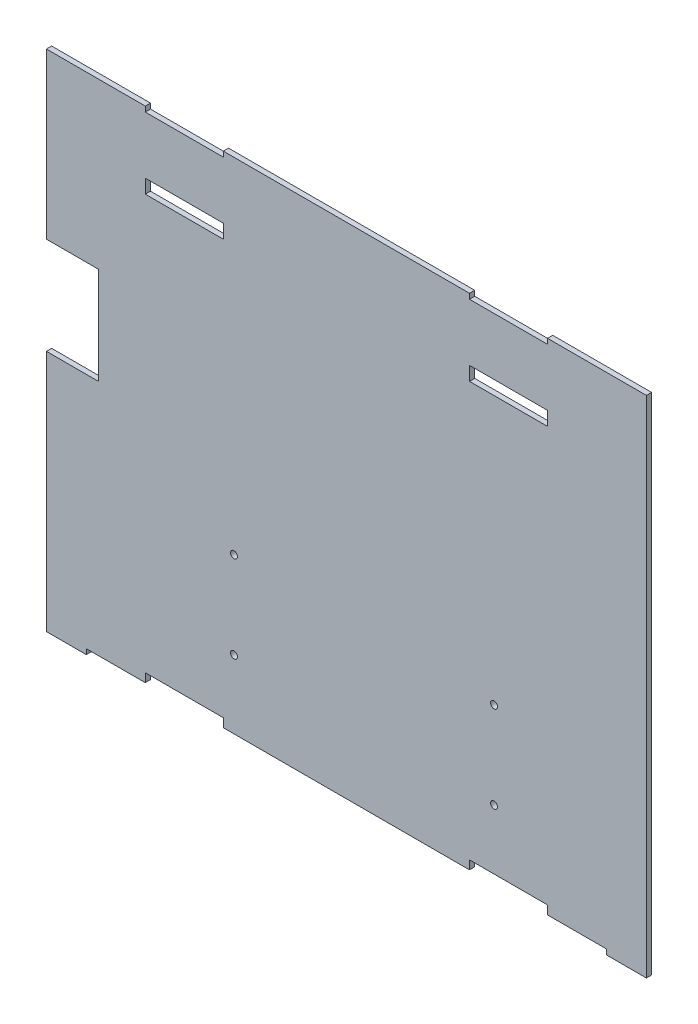
SolidWorks part; units mm, degrees
ref_plane "Piano frontale" through (0, 0, 0) normal (0, 0, 1) x (1, 0, 0)
ref_plane "Piano superiore" through (0, 0, 0) normal (0, 1, 0) x (1, 0, 0)
ref_plane "Piano destro" through (0, 0, 0) normal (1, 0, 0) x (0, 0, -1)
sketch "Schizzo1" plane through (0, 0, 0) normal (0, 0, 1) x (1, 0, 0)
  line L0 (0, 144) -> (0, -144) construction
  line L1 (173, -144) -> (-173, -144)
  line L2 (173, -144) -> (173, 144)
  line L3 (173, 144) -> (-173, 144)
  line L4 (-173, -144) -> (-173, 144)
  line L5 (173, -144) -> (-173, 144) construction
  line L6 (173, 144) -> (-173, -144) construction
  line L7 (173, -145.5) -> (150, -145.5) construction
  line L12 (161.5, -147) -> (161.5, -144) construction
  line L13 (-173, -144) -> (-150, -144)
  line L14 (150, -144) -> (150, -147)
  line L19 (-173, -144) -> (-173, -147)
  line L20 (-173, -147) -> (-150, -147)
  line L21 (-150, -144) -> (-150, -147)
  line L22 (-161.5, -147) -> (-161.5, -144) construction
  line L23 (-173, -145.5) -> (-150, -145.5) construction
  line L24 (173, -147) -> (150, -147)
  line L25 (173, -144) -> (173, -147)
  line L26 (173, -144) -> (150, -144)
  line L27 (116, -141.5) -> (71, -141.5) construction
  line L28 (-116, -144) -> (-71, -144)
  line L29 (-116, -144) -> (-116, -139)
  line L30 (-116, -139) -> (-71, -139)
  line L31 (-71, -144) -> (-71, -139)
  line L32 (-93.5, -139) -> (-93.5, -144) construction
  line L33 (-116, -141.5) -> (-71, -141.5) construction
  line L34 (93.5, -139) -> (93.5, -144) construction
  line L35 (71, -144) -> (71, -139)
  line L36 (116, -139) -> (71, -139)
  line L37 (116, -144) -> (116, -139)
  line L38 (116, -144) -> (71, -144)
  line L39 (116, 142.5) -> (71, 142.5) construction
  line L40 (-116, 108) -> (-71, 108)
  line L41 (-116, 108) -> (-116, 100)
  line L42 (-116, 100) -> (-71, 100)
  line L43 (-71, 108) -> (-71, 100)
  line L44 (-93.5, 100) -> (-93.5, 108) construction
  line L45 (-116, 104) -> (-71, 104) construction
  line L46 (-116, 144) -> (-71, 144)
  line L47 (-116, 144) -> (-116, 141)
  line L48 (-116, 141) -> (-71, 141)
  line L49 (-71, 144) -> (-71, 141)
  line L50 (-93.5, 141) -> (-93.5, 144) construction
  line L51 (-116, 142.5) -> (-71, 142.5) construction
  line L52 (93.5, 141) -> (93.5, 144) construction
  line L53 (116, 104) -> (71, 104) construction
  line L54 (93.5, 100) -> (93.5, 108) construction
  line L55 (71, 144) -> (71, 141)
  line L56 (116, 141) -> (71, 141)
  line L57 (116, 144) -> (116, 141)
  line L58 (116, 144) -> (71, 144)
  line L59 (71, 108) -> (71, 100)
  line L60 (116, 100) -> (71, 100)
  line L61 (116, 108) -> (116, 100)
  line L62 (116, 108) -> (71, 108)
  point P0 (0, 0)
  point P18 (161.5, -145.5)
  point P31 (93.5, -141.5)
  point P56 (93.5, 104)
  point P57 (93.5, 142.5)
  point P192 (-93.5, 142.5)
  point P203 (-161.5, -145.5)
  point P244 (-93.5, -141.5)
  point P314 (-93.5, 104)
  dimension "D1" = 288
  dimension "D2" = 346
  dimension "D3" = 23
  dimension "D4" = 3
  dimension "D5" = 5
  dimension "D6" = 45
  dimension "D7" = 57
  dimension "D8" = 8
  dimension "D9" = 3
  dimension "D10" = 36
extrude "Estrusione-Estrusione1" add sketch "Schizzo1" along normal blind 3 contours L24 L2 L3 L4 L20 L21 L1 L14 | L21 L1 L19 L20 | L25 L1 L14 L24
sketch "Schizzo3" plane through (0, 0, 0) normal (0, 0, -1) x (-1, 0, 0)
  line L0 (173, -147) -> (173, 144) construction
  line L1 (173, 49) -> (143, 49)
  line L2 (173, 49) -> (173, -7)
  line L3 (173, -7) -> (143, -7)
  line L4 (143, 49) -> (143, -7)
  line L5 (158, -7) -> (158, 49) construction
  line L6 (173, 21) -> (143, 21) construction
  line L7 (116, 144) -> (173, 144) construction
  point P220 (158, 21)
  dimension "D1" = 95
  dimension "D2" = 30
  dimension "D3" = 56
sketch "Schizzo2" plane through (0, 0, 3) normal (0, 0, 1) x (1, 0, 0)
  line L0 (-116, -139) -> (-71, -139) construction
  line L1 (-64.85, -54.5) -> (85.15, -54.5) construction
  line L2 (-64.85, -54.5) -> (-64.85, -104.5) construction
  line L3 (-64.85, -104.5) -> (85.15, -104.5) construction
  line L4 (85.15, -54.5) -> (85.15, -104.5) construction
  line L5 (10.15, -104.5) -> (10.15, -54.5) construction
  line L6 (-64.85, -79.5) -> (85.15, -79.5) construction
  line L8 (173, -147) -> (173, 144) construction
  circle A0 centre (-64.85, -54.5) radius 2
  circle A1 centre (85.15, -54.5) radius 2
  circle A2 centre (85.15, -104.5) radius 2
  circle A3 centre (-64.85, -104.5) radius 2
  point P100 (10.15, -79.5)
  dimension "D3" = 4
  dimension "D4" = 4
  dimension "D5" = 4
  dimension "D6" = 4
  dimension "D1" = 50
  dimension "D2" = 150
  dimension "D7" = 34.5
  dimension "D8" = 87.85
extrude "Taglio-Estrusione1" cut sketch "Schizzo2" against normal through all and the other way through all
extrude "Taglio-Estrusione2" cut sketch "Schizzo3" against normal through all contours L1 L4 L3 L2
